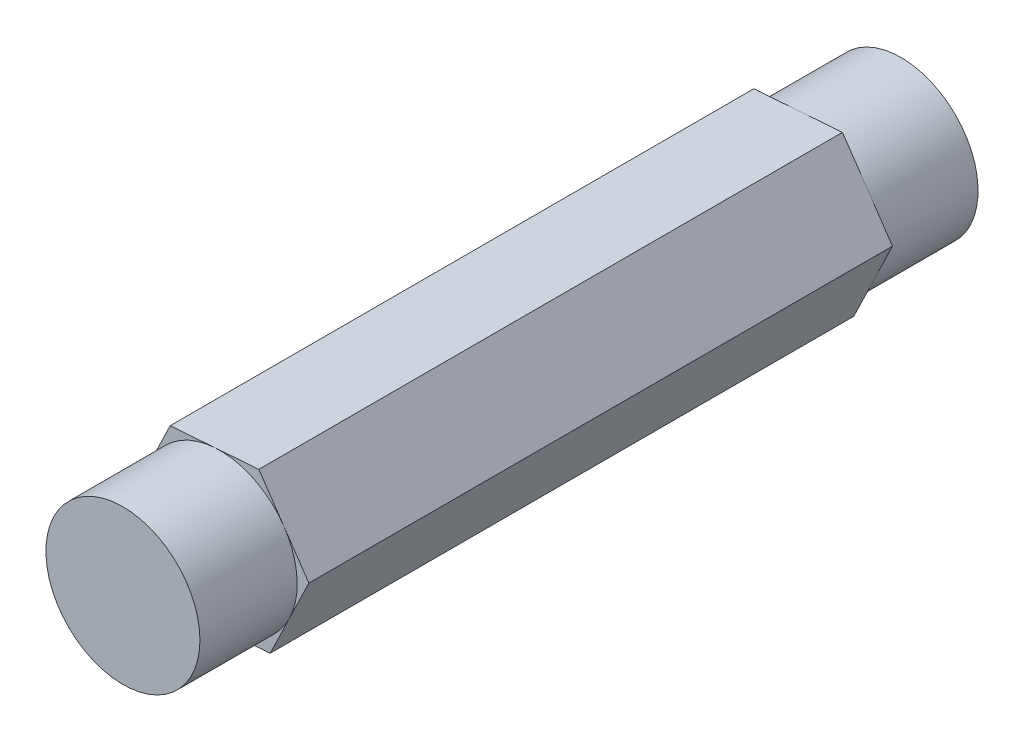
SolidWorks part; units mm, degrees
material "AISI 304"
ref_plane "前视基准面" through (0, 0, 0) normal (0, 0, 1) x (1, 0, 0)
ref_plane "上视基准面" through (0, 0, 0) normal (0, 1, 0) x (1, 0, 0)
ref_plane "右视基准面" through (0, 0, 0) normal (1, 0, 0) x (0, 0, -1)
sketch "草图3" plane through (0, 0, 0) normal (0, 0, 1) x (1, 0, 0)
  line L1 (5.4698, 0.4053) -> (2.3839, 4.9397)
  line L2 (2.3839, 4.9397) -> (-3.0859, 4.5344)
  line L3 (-3.0859, 4.5344) -> (-5.4698, -0.4053)
  line L4 (-5.4698, -0.4053) -> (-2.3839, -4.9397)
  line L5 (-2.3839, -4.9397) -> (3.0859, -4.5344)
  line L6 (3.0859, -4.5344) -> (5.4698, 0.4053)
  circle A0 centre (0, 0) radius 4.75 construction
extrude "凸台-拉伸1" add sketch "草图3" along normal blind 36
sketch "草图4" plane through (0, 0, 0) normal (0, 0, -1) x (-1, 0, 0)
  circle A0 centre (0, 0) radius 4.75
extrude "凸台-拉伸2" add sketch "草图4" along normal blind 6
sketch "草图5" plane through (0, 0, 36) normal (0, 0, 1) x (1, 0, 0)
  circle A0 centre (0, 0) radius 4.75
extrude "凸台-拉伸3" add sketch "草图5" along normal blind 6
